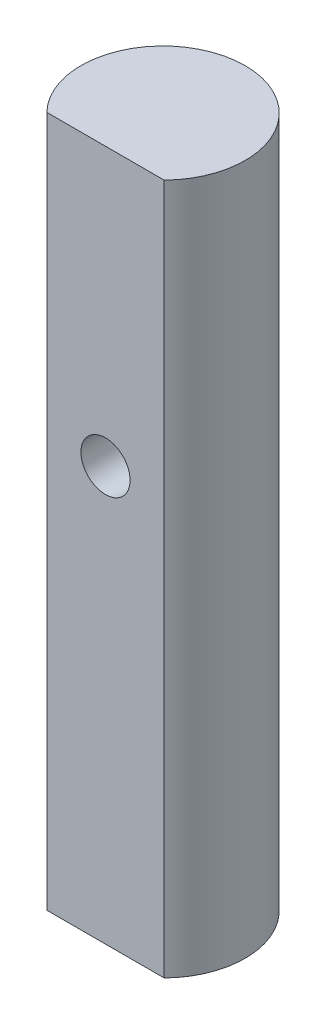
SolidWorks part; units mm, degrees
material "O-1 GS"
ref_plane "Z" through (0, 0, 0) normal (0, 0, 1) x (1, 0, 0)
ref_plane "Y" through (0, 0, 0) normal (0, 1, 0) x (1, 0, 0)
ref_plane "X" through (0, 0, 0) normal (1, 0, 0) x (0, 0, -1)
sketch "Sketch1" plane through (0, 0, 0) normal (0, 1, 0) x (1, 0, 0)
  circle A0 centre (0, 0) radius 6.35
  dimension "D1" = 12.7
extrude "Boss-Extrude1" add sketch "Sketch1" along normal blind 53.4019
sketch "Sketch2" plane through (0, 53.4019, 0) normal (0, 1, 0) x (1, 0, 0)
  line L0 (0, -6.35) -> (0, -4.445) construction
  line L1 (0, -4.445) -> (-5.6552, -4.445)
  line L2 (-5.6552, -4.445) -> (-5.6552, -6.8505)
  line L3 (-5.6552, -6.8505) -> (5.9079, -6.8505)
  line L4 (5.9079, -6.8505) -> (5.9079, -4.445)
  line L5 (5.9079, -4.445) -> (0, -4.445)
  circle A0 centre (0, 0) radius 6.35 construction
  dimension "D1" = 1.905
extrude "Cut-Extrude1" cut sketch "Sketch2" against normal through all
hole_wizard "#10-24 Tapped Hole1" positions "Sketch3" profile "Sketch4" tap size "#10-24" standard "ANSI Inch" end condition through all
sketch "Sketch3" plane through (0, 0, 4.445) normal (0, 0, 1) x (1, 0, 0)
  line L0 (4.5348, 0) -> (-4.5348, 0) construction
  point P0 (0, 31.9881)
  dimension "D1" = 31.9881
sketch "Sketch4" plane through (0, 31.9881, 4.445) normal (1, 0, 0) x (0, -1, 0)
  line L0 (0, 0) -> (0, 10.795)
  line L1 (0, 10.795) -> (1.8986, 10.795)
  line L2 (1.8986, 10.795) -> (1.8986, 0)
  line L5 (1.8986, 0) -> (0, 0)
  line L11 (0, -6.35) -> (0, 107.95) construction
  dimension "Thru Tap Drill Dia." = 3.7973
  dimension "Thru Tap Drill Depth" = 10.795
cosmetic thread "Hole Thread1" parameters "D2"=4.826
